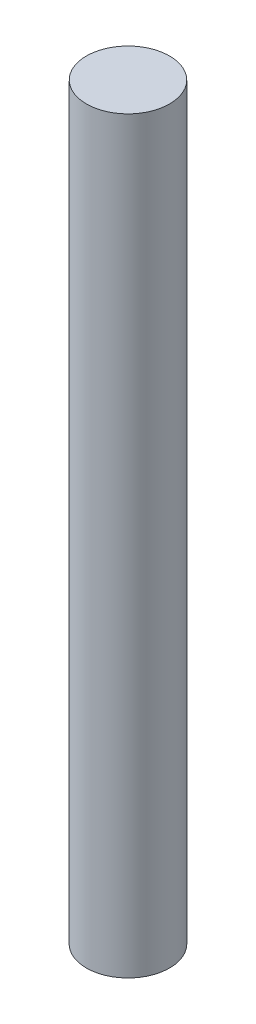
SolidWorks part; units mm, degrees
ref_plane "前视基准面" through (0, 0, 0) normal (0, 0, 1) x (1, 0, 0)
ref_plane "上视基准面" through (0, 0, 0) normal (0, 1, 0) x (1, 0, 0)
ref_plane "右视基准面" through (0, 0, 0) normal (1, 0, 0) x (0, 0, -1)
sketch "草图2" plane through (0, 0, 0) normal (0, 1, 0) x (1, 0, 0)
  circle A0 centre (0, 0) radius 2
extrude "凸台-拉伸1" add sketch "草图2" along normal blind 36
